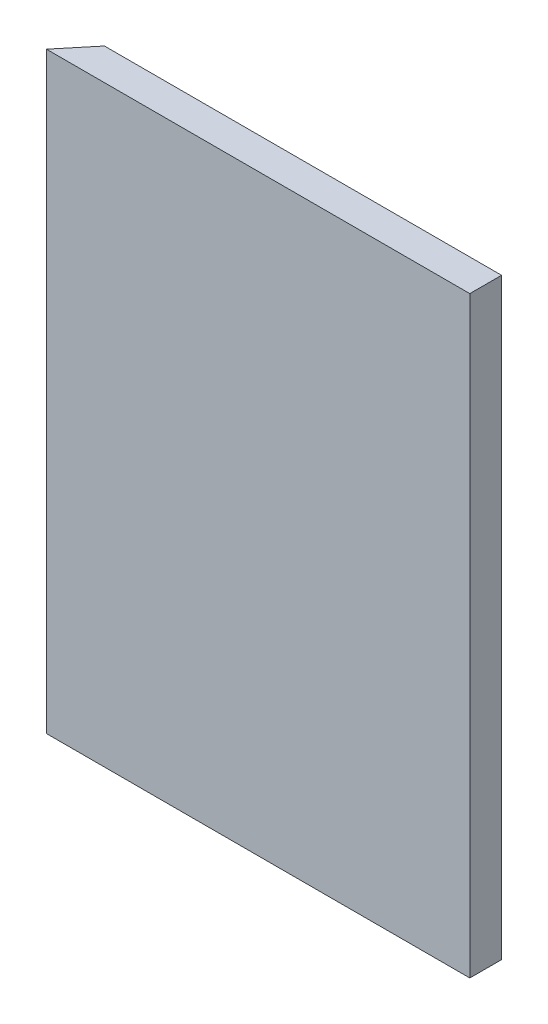
SolidWorks part; units mm, degrees
ref_plane "Front Plane" through (0, 0, 0) normal (0, 0, 1) x (1, 0, 0)
ref_plane "Top Plane" through (0, 0, 0) normal (0, 1, 0) x (1, 0, 0)
ref_plane "Right Plane" through (0, 0, 0) normal (1, 0, 0) x (0, 0, -1)
sketch "Sketch1" plane through (0, 0, 0) normal (0, 1, 0) x (1, 0, 0)
  line L1 (-6.5, 0.25) -> (3.5, 0.25)
  line L2 (-6.5, 0.25) -> (-6.5, -0.5)
  line L3 (-6.5, -0.5) -> (3.5, -0.5)
  line L4 (3.5, 0.25) -> (3.5, -0.5)
  dimension "D1" = 10
  dimension "D2" = 0.75
  dimension "D3" = 0.5
  dimension "D4" = 3.5
extrude "Boss-Extrude1" add sketch "Sketch1" along normal blind 14
sketch "Sketch2" plane through (0, 14, 0) normal (0, 1, 0) x (1, 0, 0)
  line L0 (-6.5, -0.5) -> (-5.8797, 0.25)
  line L1 (3.5, 0.25) -> (-6.5, 0.25) construction
  line L2 (-5.8797, 0.25) -> (-6.5, 0.25)
  line L3 (-6.5, 0.25) -> (-6.5, -0.5)
extrude "Cut-Extrude1" cut sketch "Sketch2" against normal through all
